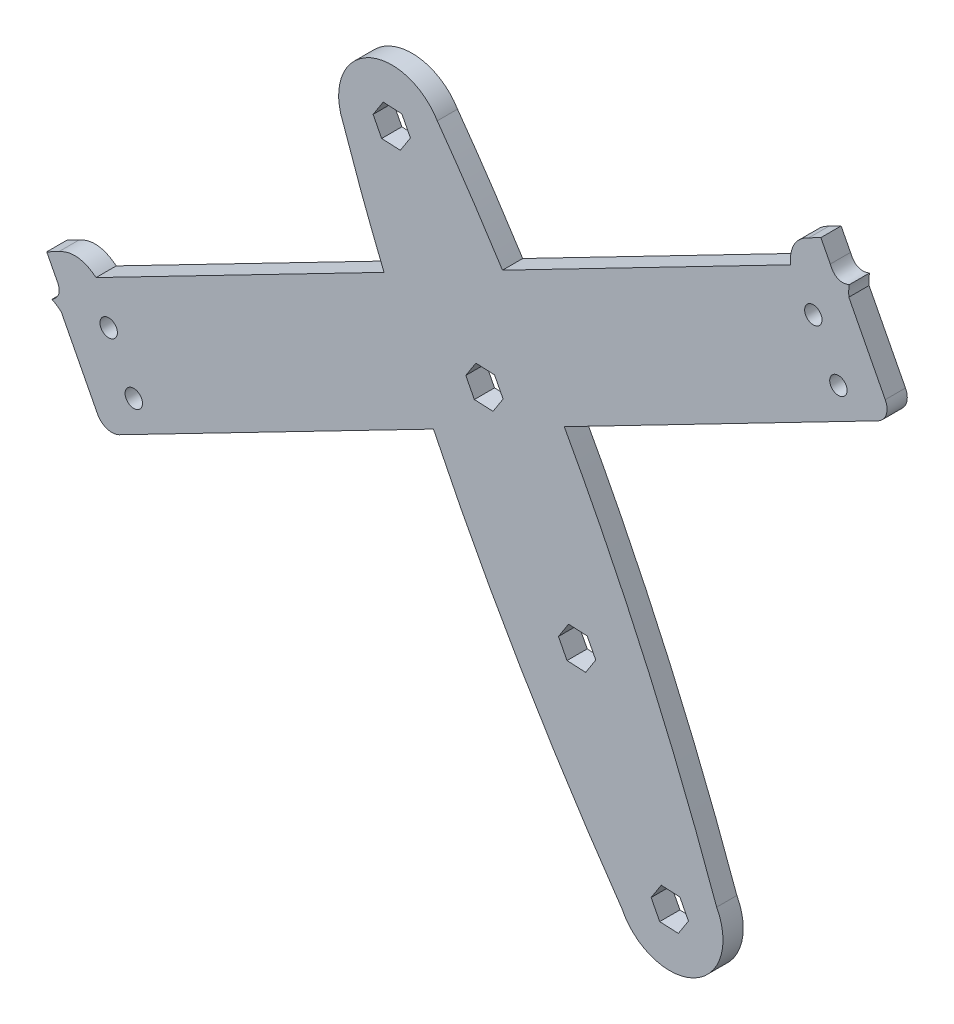
SolidWorks part; units mm, degrees
ref_plane "Front Plane" through (0, 0, 0) normal (0, 0, 1) x (1, 0, 0)
ref_plane "Top Plane" through (0, 0, 0) normal (0, 1, 0) x (1, 0, 0)
ref_plane "Right Plane" through (0, 0, 0) normal (1, 0, 0) x (0, 0, -1)
ref_plane "Plane1" through (2.4968, 3.8858, 9) normal (0, 0, -1) x (-1, 0, 0)
sketch "Sketch3" plane through (0, 0, 0) normal (0, 0, 1) x (1, 0, 0)
  line L0 (4.9031, 2.5283) -> (17.9253, -22.7256) construction
  line L1 (39.2761, -64.1313) -> (45.0513, -61.1533) construction
  line L24 (78.2627, -131.0102) -> (76.1459, -126.905)
  line L25 (76.1459, -126.905) -> (71.5323, -126.6857)
  line L26 (71.5323, -126.6857) -> (69.0355, -130.5715)
  line L27 (69.0355, -130.5715) -> (71.1523, -134.6766)
  line L28 (71.1523, -134.6766) -> (75.7659, -134.896)
  line L29 (75.7659, -134.896) -> (78.2627, -131.0102)
  line L30 (55.3474, -86.5705) -> (53.2305, -82.4653)
  line L31 (53.2305, -82.4653) -> (48.617, -82.246)
  line L32 (48.617, -82.246) -> (46.1202, -86.1318)
  line L33 (46.1202, -86.1318) -> (48.237, -90.2369)
  line L34 (48.237, -90.2369) -> (52.8506, -90.4563)
  line L35 (52.8506, -90.4563) -> (55.3474, -86.5705)
  line L36 (32.4321, -42.1308) -> (30.3152, -38.0256)
  line L37 (30.3152, -38.0256) -> (25.7016, -37.8062)
  line L38 (25.7016, -37.8062) -> (23.2049, -41.6921)
  line L39 (23.2049, -41.6921) -> (25.3217, -45.7972)
  line L40 (25.3217, -45.7972) -> (29.9353, -46.0166)
  line L41 (29.9353, -46.0166) -> (32.4321, -42.1308)
  line L42 (9.5167, 2.3089) -> (7.3999, 6.4141)
  line L43 (7.3999, 6.4141) -> (2.7863, 6.6335)
  line L44 (2.7863, 6.6335) -> (0.2895, 2.7477)
  line L45 (0.2895, 2.7477) -> (2.4064, -1.3575)
  line L46 (2.4064, -1.3575) -> (7.02, -1.5769)
  line L47 (7.02, -1.5769) -> (9.5167, 2.3089)
  arc A0 (16.1611, 9.2966) -> (-7.1395, -2.7183) centre (4.9031, 2.5283) ccw
  arc A1 (61.8431, -136.6063) -> (85.2333, -124.5451) centre (73.6491, -130.7908) ccw
  spline S0 degree 3 poles (16.1611, 9.2966) (45.5997, -31.6323) (68.2562, -77.1635) (85.2333, -124.5451) knots 0 0 0 0 1 1 1 1
  spline S1 degree 3 poles (-7.1395, -2.7183) (9.1328, -50.4365) (33.0874, -95.2983) (61.8431, -136.6063) knots 0 0 0 0 1 1 1 1
extrude "Boss-Extrude1" add sketch "Sketch3" along normal blind 5
sketch "Sketch4" plane through (0, 0, 5) normal (0, 0, 1) x (1, 0, 0)
  line L0 (8.1678, -43.9362) -> (16.5699, -39.6036) construction
  line L1 (31.3876, -48.8397) -> (-62.4507, -97.2274)
  line L3 (38.1336, -61.9156) -> (33.7816, -53.48) construction
  line L4 (17.6384, -22.1759) -> (-68.216, -66.4467)
  line L5 (17.6273, -22.1816) -> (103.4634, 22.1249)
  line L6 (113.3327, 27.2191) -> (111.0101, 31.7234)
  line L7 (31.3876, -48.8397) -> (125.2058, -0.4131)
  line L9 (126.9255, 4.976) -> (117.9223, 22.4181)
  line L10 (111.0101, 31.7234) -> (108.0072, 30.175)
  line L11 (-80.4119, -67.0336) -> (-77.4097, -65.4839)
  line L12 (-67.8391, -95.5054) -> (-76.835, -78.0596)
  line L13 (-78.0874, -71.5369) -> (-80.4119, -67.0336)
  arc A0 (-62.4507, -97.2274) -> (-67.8391, -95.5054) centre (-64.2839, -93.6722) cw
  circle A1 centre (109.1398, 14.255) radius 2.15
  circle A2 centre (115.3407, 2.2296) radius 2.15
  circle A3 centre (-58.8868, -87.6565) radius 2.15
  arc A5 (125.2058, -0.4131) -> (126.9255, 4.976) centre (123.3711, 3.1413) ccw
  circle A6 centre (-65.0927, -75.6336) radius 2.15
  parabola Q2 (108.0072, 30.175) -> (103.4634, 22.1249) focus (107.5564, 25.5843) apex (104.7354, 27.4923)
  parabola Q3 (117.9223, 22.4181) -> (118.0232, 25.1472) focus (121.4679, 26.268) apex (119.257, 28.0125)
  parabola Q4 (-76.835, -78.0596) -> (-79.1175, -76.56) focus (-82.0273, -78.7177) apex (-82.1675, -75.9049)
  parabola Q5 (-77.4097, -65.4839) -> (-68.216, -66.4467) focus (-73.4074, -67.7771) apex (-73.3274, -64.3724)
  spline S0 degree 2 poles (118.0971, 25.177) (114.7575, 23.8112) (113.3327, 27.2191) knots 0 0 0 1 1 1
  spline S1 degree 2 poles (-79.1845, -76.6031) (-76.136, -74.6731) (-78.0874, -71.5369) knots 0 0 0 1 1 1
  point P5 (-77.6983, -88.213)
  point P11 (126.6969, 17.237)
  point P15 (119.8168, 30.5661)
  point P18 (133.5771, 3.908)
  point P21 (-70.8237, -101.5449)
  point P24 (-84.5729, -74.8811)
  point P52 (-70.8237, -101.5449)
  point P53 (-84.5729, -74.8811)
  dimension "D1" = 15
  dimension "D2" = 115
extrude "Boss-Extrude2" add sketch "Sketch4" against normal up to surface (5 mm away)
